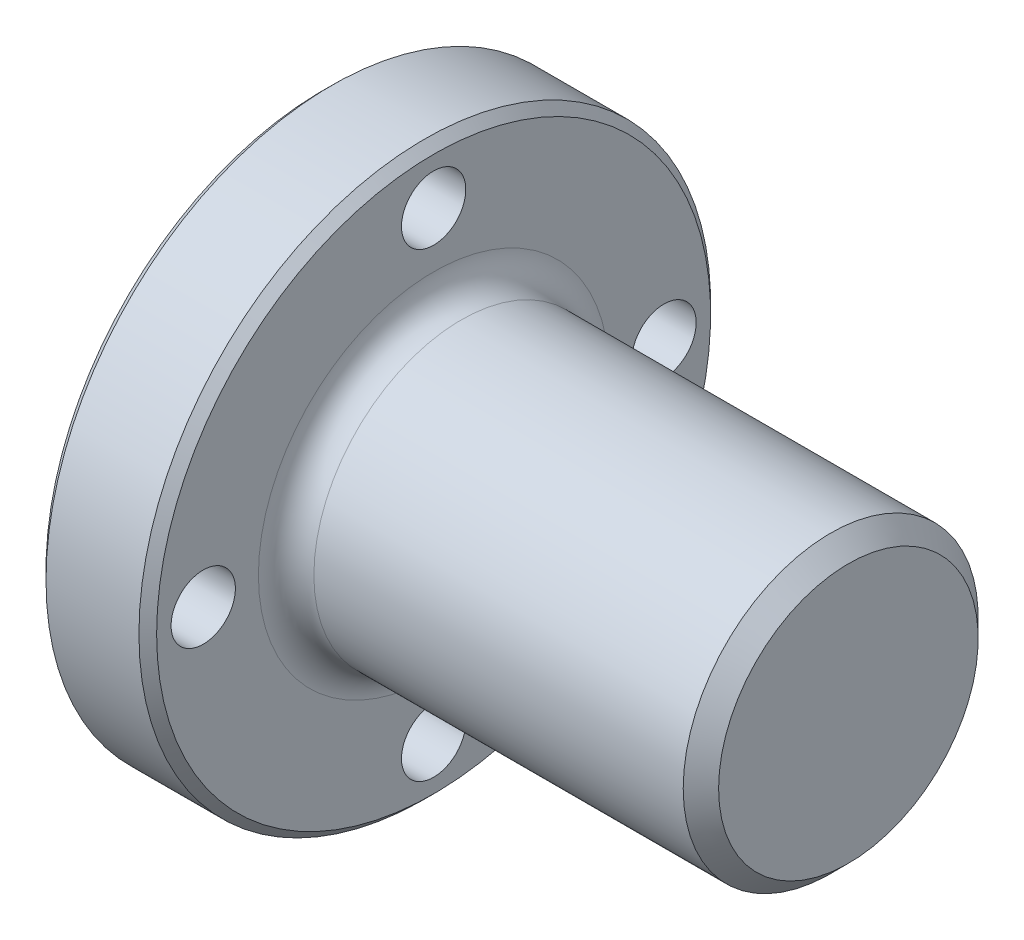
SolidWorks part; units mm, degrees
ref_plane "Front Plane" through (0, 0, 0) normal (1, 0, 0) x (0, 1, 0)
ref_plane "Top Plane" through (0, 0, 0) normal (0, 0, 1) x (0, 1, 0)
ref_plane "Right Plane" through (0, 0, 0) normal (0, 1, 0) x (-1, 0, 0)
sketch "Sketch1" plane through (0, 0, 0) normal (0, 0, 1) x (0, 1, 0)
  line L0 (0, 0) -> (8.7122, 0)
  line L1 (8.7122, 0) -> (8.7122, -4.826)
  line L2 (8.7122, -4.826) -> (24.6126, -4.826)
  line L3 (24.6126, -4.826) -> (24.6126, -14.351)
  line L4 (24.6126, -14.351) -> (12.7, -14.351)
  line L5 (12.7, -14.351) -> (12.7, -50.0634)
  line L6 (12.7, -50.0634) -> (0, -50.0634)
  line L7 (0, -50.0634) -> (0, 0)
  line L8 (0, 25.4) -> (0, -75.4634) construction
revolve "Revolve1" add sketch "Sketch1" angle 360 about L8
sketch "Sketch2" plane through (0, 0, 0) normal (1, 0, 0) x (0, 1, 0)
  circle A0 centre (19.8374, 0) radius 2.7686
extrude "Cut-Extrude2" cut sketch "Sketch2" along normal through all from offset 4.826
sketch "Sketch3" plane through (0, 0, 0) normal (1, 0, 0) x (0, 1, 0)
  circle A0 centre (0, 19.8374) radius 2.7686
  circle A1 centre (-19.8374, 0) radius 2.7686
  circle A2 centre (0, -19.8374) radius 2.7686
extrude "Cut-Extrude4" cut sketch "Sketch3" along normal through all from offset 4.826
fillet "Fillet1" radius 2.3876 1 edges at (14.351, 0, 12.7)
chamfer "Chamfer1" distance 0.762 angle 45 2 edges at (14.351, 0, 24.6126) (4.826, 0, 24.6126)
chamfer "Chamfer2" distance 1.524 angle 45 1 edges at (50.0634, 0, 12.7)
